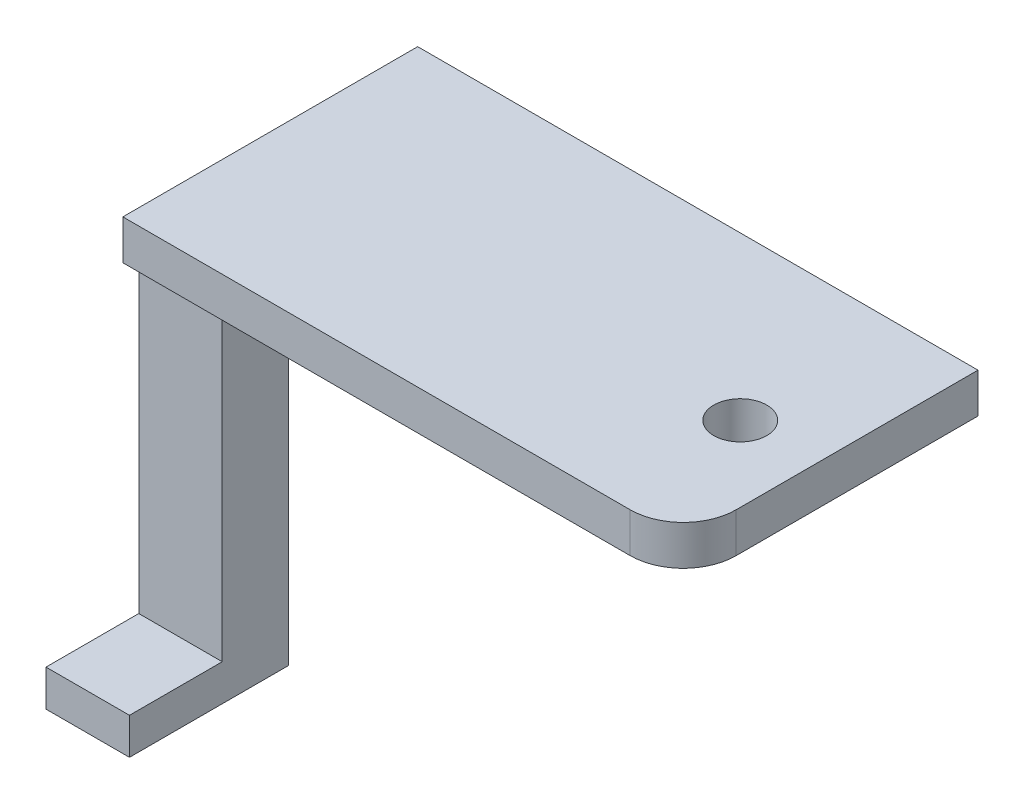
SolidWorks part; units mm, degrees
ref_plane "Front Plane" through (0, 0, 0) normal (0, 0, 1) x (1, 0, 0)
ref_plane "Top Plane" through (0, 0, 0) normal (0, 1, 0) x (1, 0, 0)
ref_plane "Right Plane" through (0, 0, 0) normal (1, 0, 0) x (0, 0, -1)
sketch "Sketch1" plane through (0, 0, 0) normal (0, 1, 0) x (1, 0, 0)
  line L0 (-42.2847, 10) -> (0, 10) construction
  line L1 (-4, 0) -> (-42.2847, 0)
  line L2 (0, 4) -> (0, 20)
  line L3 (-39.1347, 20) -> (-42.2847, 20)
  line L4 (-42.2847, 0) -> (-42.2847, 20)
  line L5 (-39.1347, 0.3996) -> (-39.1347, 89.8689) construction
  line L6 (-42.2847, 0) -> (-35.9847, 0)
  line L7 (-42.2847, 0) -> (-42.2847, 5)
  line L8 (-42.2847, 5) -> (-35.9847, 5)
  line L9 (-35.9847, 0) -> (-35.9847, 5)
  line L11 (-42.2847, 20) -> (-39.1347, 20)
  line L12 (-42.2847, 20) -> (-42.2847, 22.25)
  line L13 (-42.2847, 22.25) -> (0, 22.25)
  line L14 (0, 20) -> (0, 22.25)
  arc A0 (-4, 0) -> (0, 4) centre (-4, 4) ccw
  circle A2 centre (-5.69, 10) radius 2
  point P7 (0, 0)
  point P19 (-39.1347, 5)
  dimension "D1" = 4
  dimension "D5" = 4
  dimension "D2" = 20
  dimension "D3" = 5
  dimension "D4" = 10
  dimension "D6" = 5.69
  dimension "D7" = 6.3
  dimension "D8" = 2.25
  dimension "D9" = 22.25
extrude "Boss-Extrude1" add sketch "Sketch1" along normal blind 3 contours L1 L9 L8 L4 | L1 A0 L2 L3 L4 L8 L9 A2
sketch "Sketch4" plane through (0, 0, 0) normal (0, -1, 0) x (1, 0, 0)
  line L0 (-42.2847, 0) -> (-42.2847, -22.25) construction
  line L1 (-42.2847, -1.2) -> (-35.9847, -1.2)
  line L2 (-42.2847, -1.2) -> (-42.2847, -6.2)
  line L3 (-42.2847, -6.2) -> (-35.9847, -6.2)
  line L4 (-35.9847, -1.2) -> (-35.9847, -6.2)
  line L5 (-4, 0) -> (-42.2847, 0) construction
  dimension "D1" = 6.3
  dimension "D2" = 5
  dimension "D3" = 1.2
extrude "Boss-Extrude3" add sketch "Sketch4" along normal blind 23.525
sketch "Sketch5" plane through (0, -23.525, 0) normal (0, -1, 0) x (-1, 0, 0)
  line L1 (42.2847, 6.2) -> (35.9847, 6.2)
  line L2 (42.2847, 6.2) -> (42.2847, -5.8)
  line L3 (42.2847, -5.8) -> (35.9847, -5.8)
  line L4 (35.9847, 6.2) -> (35.9847, -5.8)
  point P6 (0, 0)
  dimension "D1" = 12
  dimension "D2" = 6.3
extrude "Boss-Extrude4" add sketch "Sketch5" along normal blind 2.75
